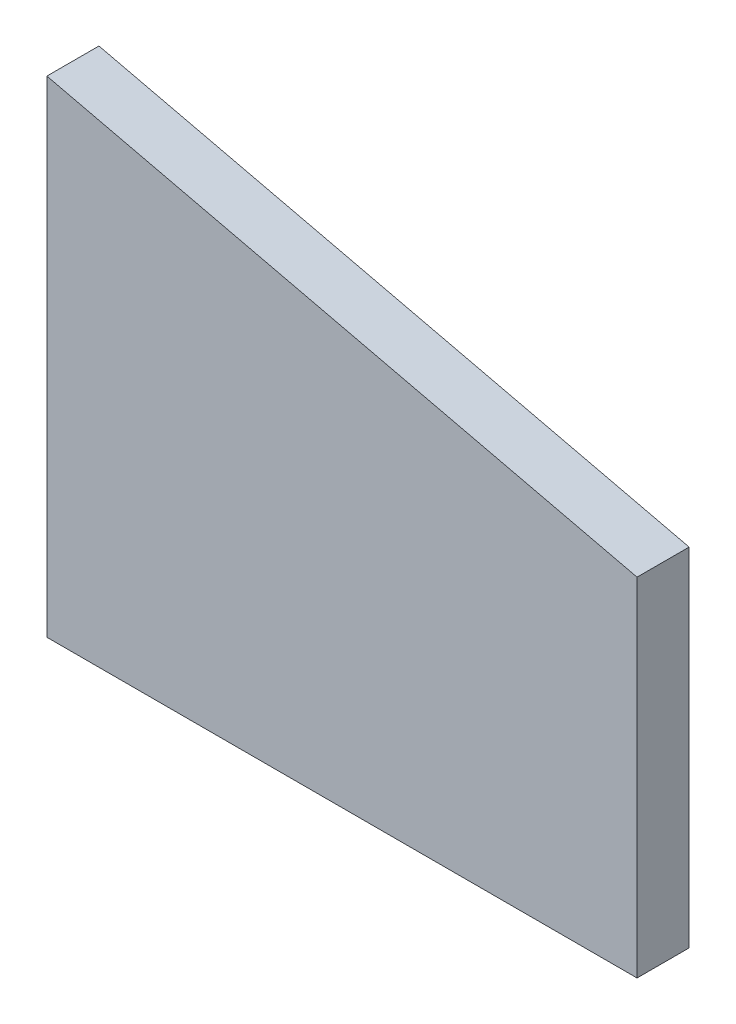
SolidWorks part; units mm, degrees
ref_plane "Front Plane" through (0, 0, 0) normal (0, 0, 1) x (1, 0, 0)
ref_plane "Top Plane" through (0, 0, 0) normal (0, 1, 0) x (1, 0, 0)
ref_plane "Right Plane" through (0, 0, 0) normal (1, 0, 0) x (0, 0, -1)
sketch "Sketch1" plane through (0, 0, 0) normal (0, 0, 1) x (1, 0, 0)
  line L0 (0, 0) -> (215.9, 0)
  line L1 (215.9, 0) -> (215.9, 127)
  line L2 (0, 0) -> (0, 177.8)
  line L3 (0, 177.8) -> (215.9, 127)
  dimension "D1" = 177.8
  dimension "D2" = 215.9
  dimension "D3" = 127
  dimension "D4" = 103.241
extrude "Boss-Extrude1" add sketch "Sketch1" along normal blind 19.05
